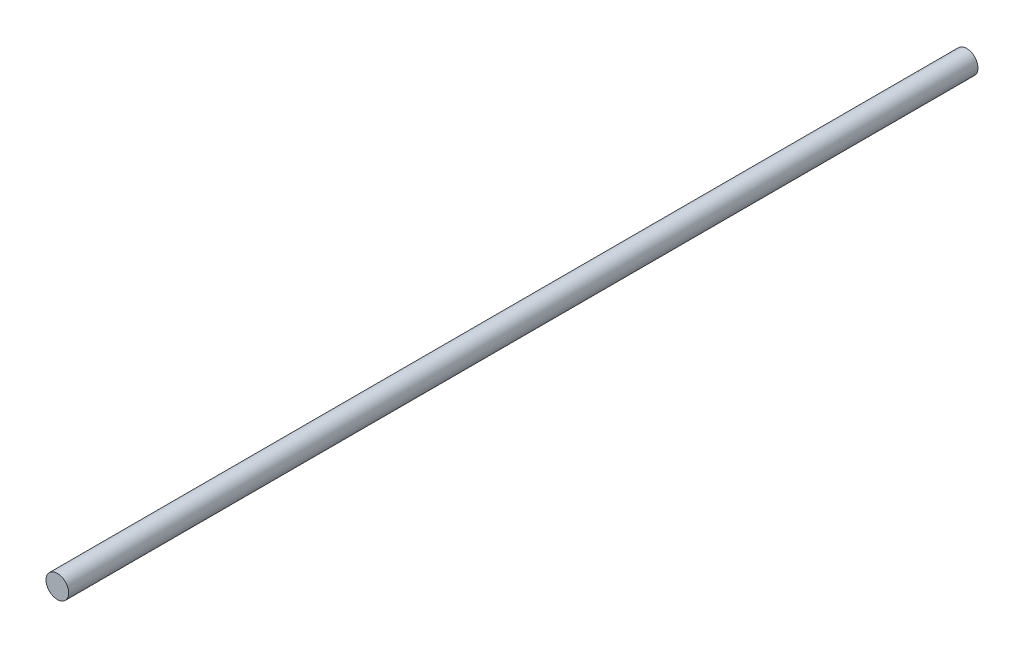
SolidWorks part; units mm, degrees
ref_plane "Front Plane" through (0, 0, 0) normal (0, 0, 1) x (1, 0, 0)
ref_plane "Top Plane" through (0, 0, 0) normal (0, 1, 0) x (1, 0, 0)
ref_plane "Right Plane" through (0, 0, 0) normal (1, 0, 0) x (0, 0, -1)
sketch "Sketch1" plane through (0, 0, 0) normal (0, 0, 1) x (1, 0, 0)
  circle A0 centre (0, 0) radius 50
  dimension "D1" = 100
extrude "Boss-Extrude1" add sketch "Sketch1" along normal blind 4000
